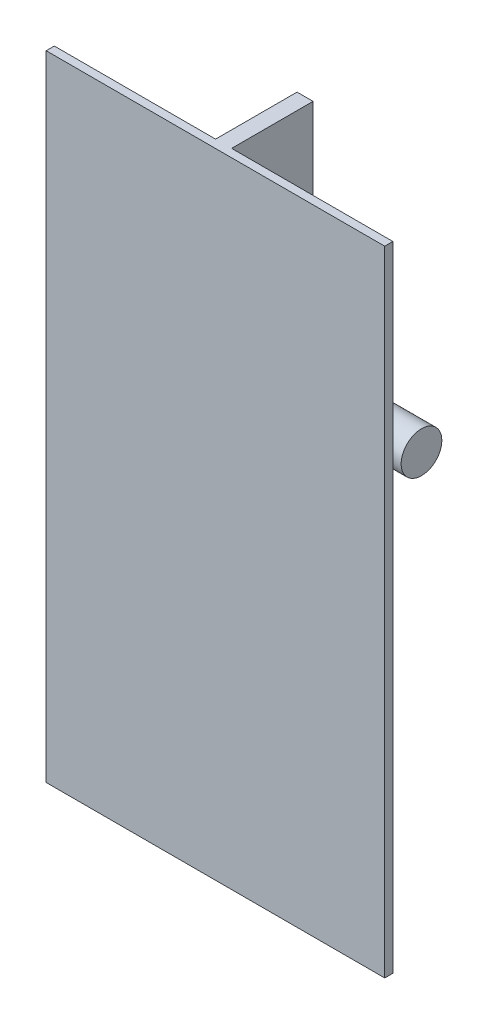
SolidWorks part; units mm, degrees
ref_plane "Front Plane" through (0, 0, 0) normal (0, 0, 1) x (1, 0, 0)
ref_plane "Top Plane" through (0, 0, 0) normal (0, 1, 0) x (1, 0, 0)
ref_plane "Right Plane" through (0, 0, 0) normal (1, 0, 0) x (0, 0, -1)
sketch "Sketch1" plane through (0, 0, 0) normal (0, 0, 1) x (1, 0, 0)
  line L1 (-105.5846, -201.4985) -> (105.58, -201.4985)
  line L2 (-105.5846, -201.4985) -> (-105.5846, 193.7642)
  line L3 (-105.5846, 193.7642) -> (105.58, 193.7642)
  line L4 (105.58, -201.4985) -> (105.58, 193.7642)
  point P4 (74.7956, 125.4629)
  point P5 (0, 0)
  point P6 (-75.0513, -184.1786)
  point P7 (105.58, 196.2221)
  point P8 (-85.4827, 193.7642)
  point P9 (0, 0)
  point P10 (-105.5846, -201.4985)
extrude "Boss-Extrude1" add sketch "Sketch1" along normal blind 5.08
sketch "Sketch2" plane through (0, 0, 0) normal (0, 0, -1) x (-1, 0, 0)
  line L0 (105.5846, -201.4985) -> (-105.58, -201.4985) construction
  line L1 (-5, -201.4985) -> (5, -201.4985)
  line L2 (-5, -201.4985) -> (-5, 193.7642)
  line L3 (-5, 193.7642) -> (5, 193.7642)
  line L4 (5, -201.4985) -> (5, 193.7642)
  line L5 (-105.58, 193.7642) -> (105.5846, 193.7642) construction
extrude "Boss-Extrude2" add sketch "Sketch2" along normal blind 50.8
sketch "Sketch3" plane through (5, 0, 0) normal (1, 0, 0) x (0, 0, -1)
  circle A0 centre (26.7091, -90.7578) radius 12.7
  point P2 (26.1306, -111.4005)
  point P3 (26.7091, -90.7578)
extrude "Cut-Extrude1" cut sketch "Sketch3" against normal blind 15
sketch "Sketch5" plane through (0, 0, -50.8) normal (0, 0, -1) x (-1, 0, 0)
  line L1 (-3.5074, 63.9206) -> (4.055, 63.9206)
  line L2 (-3.5074, 63.9206) -> (-3.5074, -36.1836)
  line L3 (-3.5074, -36.1836) -> (4.055, -36.1836)
  line L4 (4.055, 63.9206) -> (4.055, -36.1836)
  point P4 (0, 0)
extrude "Boss-Extrude3" add sketch "Sketch5" along normal blind 30
sketch "Sketch12" plane through (3.5074, 0, 0) normal (1, 0, 0) x (0, 0, -1)
  line L0 (65.8, -36.1836) -> (80.8, 13.8685)
  line L1 (80.8, -36.1836) -> (50.8, -36.1836) construction
  line L2 (80.8, 63.9206) -> (80.8, -36.1836) construction
  line L3 (80.8, 13.8685) -> (-86.2141, 63.9206)
  line L4 (80.8, 63.9206) -> (50.8, 63.9206) construction
  line L5 (-86.2141, 63.9206) -> (80.8, 63.9206)
  line L6 (80.8, 63.9206) -> (80.8, -36.1836)
  line L7 (80.8, -36.1836) -> (65.8, -36.1836)
  line M3 (50.8, -36.1836) -> (80.8, -36.1836)
  line M4 (80.8, -36.1836) -> (80.8, 63.9206)
  line M5 (80.8, 63.9206) -> (50.8, 63.9206)
extrude "Cut-Extrude4" cut sketch "Sketch12" against normal blind 20 contours L0 M3 M4 | L3 M4 M5
sketch "Sketch13" plane through (-4.055, 0, 0) normal (-1, 0, 0) x (0, 0, 1)
  circle A0 centre (-69.7441, 15.7465) radius 12.7
  point P3 (-25.1844, 18.013)
  point P4 (-25.1844, 18.013)
  point P5 (-25.1844, 18.013)
  point P6 (-25.1844, 18.013)
  point P7 (-25.1844, 18.013)
  point P8 (-25.1844, 18.013)
  point P9 (-25.1844, 18.013)
  point P10 (-25.1844, 18.013)
  point P11 (-25.1844, 18.013)
  point P12 (-69.7441, 15.7465)
extrude "Boss-Extrude4" add sketch "Sketch13" along normal blind 50
sketch "Sketch15" plane through (3.5074, 0, 0) normal (1, 0, 0) x (0, 0, -1)
  circle A0 centre (69.9048, 18.963) radius 12.7
  point P3 (25.1844, 18.013)
  point P4 (72.0618, 20.4033)
  point P5 (70.7267, 19.7262)
  point P6 (69.9048, 18.963)
extrude "Boss-Extrude5" add sketch "Sketch15" along normal blind 50 separate body
sketch "Sketch16" plane through (5, 0, 0) normal (1, 0, 0) x (0, 0, -1)
  circle A0 centre (26.7091, -90.7578) radius 12.7
extrude "Boss-Extrude6" add sketch "Sketch16" along normal blind 50 separate body
sketch "Sketch17" plane through (-5, 0, 0) normal (-1, 0, 0) x (0, 0, 1)
  circle A0 centre (-26.7091, -90.7578) radius 12.7
extrude "Boss-Extrude7" add sketch "Sketch17" along normal blind 50 separate body
